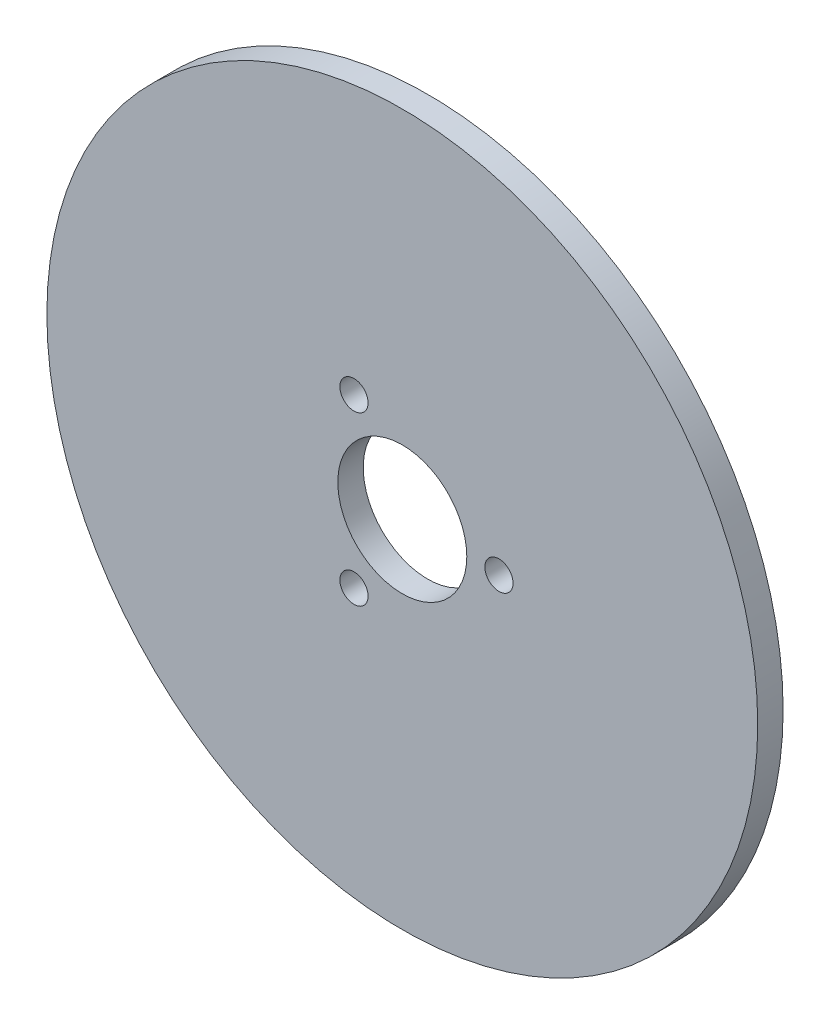
SolidWorks part; units mm, degrees
ref_plane "Front Plane" through (0, 0, 0) normal (0, 0, 1) x (1, 0, 0)
ref_plane "Top Plane" through (0, 0, 0) normal (0, 1, 0) x (1, 0, 0)
ref_plane "Right Plane" through (0, 0, 0) normal (1, 0, 0) x (0, 0, -1)
sketch "Sketch1" plane through (0, 0, 0) normal (0, 0, 1) x (1, 0, 0)
  circle A0 centre (0, 0) radius 12.7
  circle A1 centre (0, 0) radius 70
  dimension "D1" = 25.4
  dimension "D2" = 140
extrude "Boss-Extrude1" add sketch "Sketch1" along normal blind 5
sketch "Sketch3" plane through (0, 0, 5) normal (0, 0, 1) x (1, 0, 0)
  line L0 (0, 0) -> (-42.1591, 0) construction
  line L1 (0, 0) -> (0, 50000) construction
  circle A0 centre (0, 0) radius 19.0341 construction
  circle A1 centre (-9.5171, 16.484) radius 2.7781
  circle A2 centre (19.0341, 0) radius 2.7781
  circle A3 centre (-9.5171, -16.484) radius 2.7781
  circle A4 centre (0, 0) radius 12.7 construction
  point P16 (0, 0)
  dimension "D1" = 6.3341
  dimension "D2" = 5.5562
  dimension "D3" = 3
extrude "Cut-Extrude1" cut sketch "Sketch3" against normal through all both
